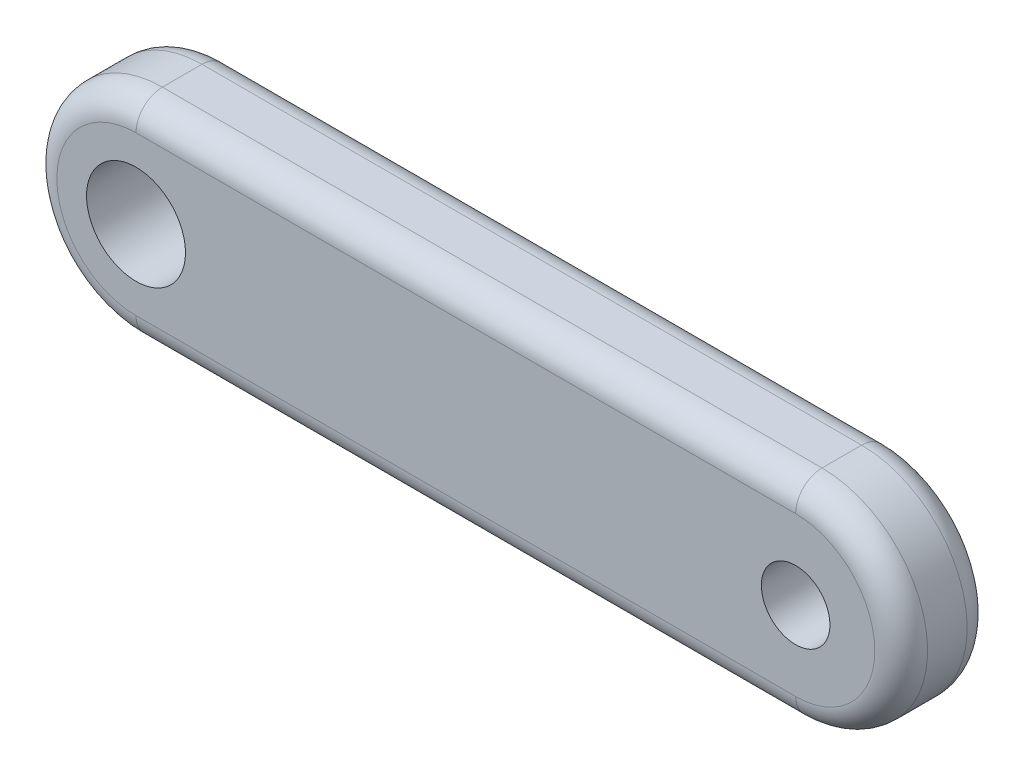
SolidWorks part; units mm, degrees
material "ABS"
ref_plane "Front Plane" through (0, 0, 0) normal (0, 0, 1) x (1, 0, 0)
ref_plane "Top Plane" through (0, 0, 0) normal (0, 1, 0) x (1, 0, 0)
ref_plane "Right Plane" through (0, 0, 0) normal (1, 0, 0) x (0, 0, -1)
sketch "Sketch1" plane through (0, 0, 0) normal (0, 0, 1) x (1, 0, 0)
  line L0 (0, 0) -> (31.75, 0) construction
  line L1 (0, 5.08) -> (31.75, 5.08)
  line L2 (0, -5.08) -> (31.75, -5.08)
  arc A0 (0, 5.08) -> (0, -5.08) centre (0, 0) ccw
  arc A1 (31.75, -5.08) -> (31.75, 5.08) centre (31.75, 0) ccw
  circle A2 centre (0, 0) radius 2.3813
  circle A3 centre (31.75, 0) radius 1.651
  point P3 (15.875, 0)
  dimension "D2" = 4.7625
  dimension "D3" = 3.302
  dimension "D1" = 10.16
  dimension "D4" = 31.75
extrude "Boss-Extrude1" add sketch "Sketch1" along normal blind 4.445
fillet "Fillet1" radius 1.27 8 edges at (36.83, 0, 0) (15.875, -5.08, 0) (-5.08, 0, 0) (36.83, 0, 4.445) (15.875, -5.08, 4.445) (-5.08, 0, 4.445) (15.875, 5.08, 0) (15.875, 5.08, 4.445)
